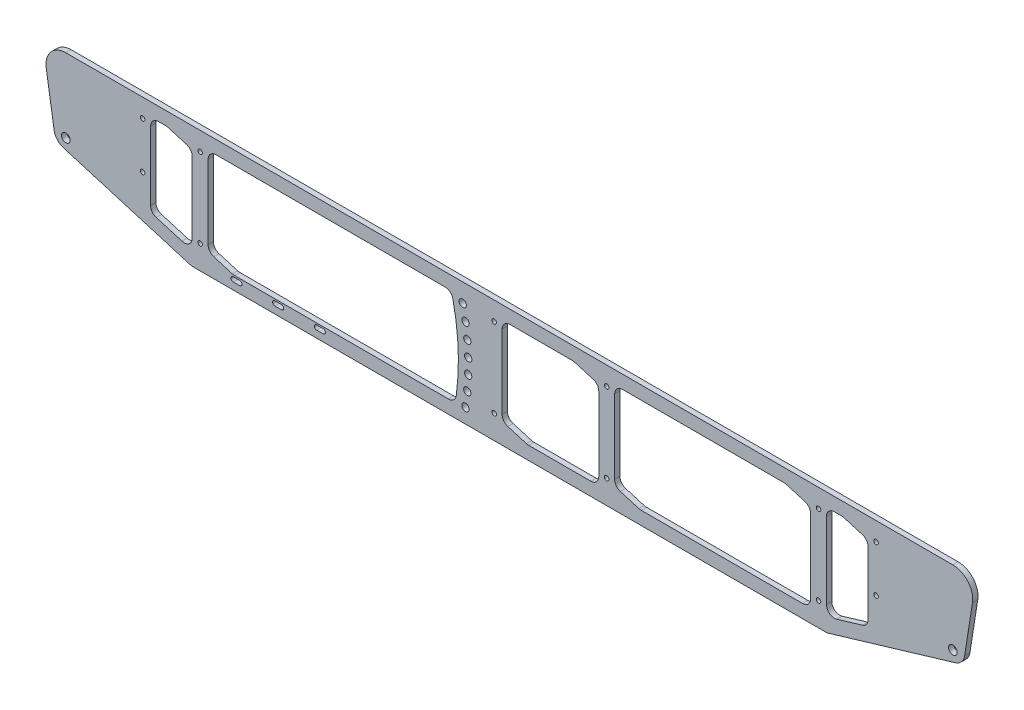
SolidWorks part; units mm, degrees
material "Сплав 2024"
ref_plane "Спереди" through (0, 0, 0) normal (0, 0, 1) x (1, 0, 0)
ref_plane "Сверху" through (0, 0, 0) normal (0, 1, 0) x (1, 0, 0)
ref_plane "Справа" through (0, 0, 0) normal (1, 0, 0) x (0, 0, -1)
sketch "Эскиз1" plane through (0, 0, 0) normal (0, 0, 1) x (1, 0, 0)
  line L0 (-349.8183, 28.6724) -> (-342.9109, -15.3036)
  line L1 (-350, 46) -> (350, 46) construction
  line L2 (-350, 46) -> (-350, -46) construction
  line L3 (-350, -46) -> (350, -46) construction
  line L4 (350, 46) -> (350, -46) construction
  line L5 (-350, 46) -> (350, -46) construction
  line L6 (-350, -46) -> (350, 46) construction
  line L7 (-342.9109, -15.3036) -> (-240, -46)
  line L9 (0, 62.4154) -> (0, -74.3401) construction
  line L10 (-240, -46) -> (240, -46)
  line L12 (-335, 46) -> (335, 46)
  line L15 (342.9109, -15.3036) -> (240, -46)
  line L16 (349.8183, 28.6724) -> (342.9109, -15.3036)
  arc A0 (-335, 46) -> (-349.8183, 28.6724) centre (-335, 31) ccw
  arc A1 (335, 46) -> (349.8183, 28.6724) centre (335, 31) cw
  circle A2 centre (-335, -9.6353) radius 3.25
  circle A3 centre (335, -9.6353) radius 3.25
  point P0 (0, 0)
  point P20 (0, 46)
  point P21 (0, -46)
  dimension "D3" = 30
  dimension "D4" = 6.5
  dimension "D1" = 700
  dimension "D2" = 92
  dimension "D5" = 480
extrude "Бобышка-Вытянуть1" add sketch "Эскиз1" along normal blind 4
sketch "Эскиз2" plane through (0, 0, 4) normal (0, 0, 1) x (1, 0, 0)
  line L0 (0, 49.4785) -> (0, -75.5602) construction
  line L1 (-350, 31) -> (-320, 31) construction
  line L2 (-335, 46) -> (-335, 16) construction
  line L3 (335, 46) -> (335, 16) construction
  line L4 (350, 31) -> (320, 31) construction
  circle A0 centre (-335, 31) radius 15 construction
  arc A1 (-335, 46) -> (-349.8183, 28.6724) centre (-335, 31) ccw construction
  circle A2 centre (-335, 31) radius 10 construction
  circle A4 centre (335, 31) radius 10 construction
  circle A5 centre (335, 31) radius 15 construction
  dimension "D2" = 20
hole_wizard "Отверстие с зазором M32" [suppressed] positions "Эскиз4" profile "Эскиз3" hole size "M3" standard "Ansi Metric"
sketch "Эскиз4" plane through (0, 0, 4) normal (0, 0, 1) x (1, 0, 0)
  line L0 (-335, 46) -> (-335, 16) construction
  line L1 (-350, 31) -> (-320, 31) construction
  line L2 (350, 31) -> (320, 31) construction
  line L3 (335, 46) -> (335, 16) construction
  circle A0 centre (-335, 31) radius 10 construction
  circle A1 centre (335, 31) radius 10 construction
  point P0 (-335, 41)
  point P6 (-345, 31)
  point P10 (-335, 21)
  point P12 (-325, 31)
  point P34 (325, 31)
  point P40 (335, 41)
  point P44 (345, 31)
  point P46 (335, 21)
sketch "Эскиз3" plane through (-335, 41, 4) normal (1, 0, 0) x (0, -1, 0)
  line L0 (0, 0) -> (0, 4)
  line L1 (0, 4) -> (1.7, 4)
  line L2 (1.7, 4) -> (1.7, 0)
  line L5 (1.7, 0) -> (0, 0)
  line L11 (0, -6.35) -> (0, 107.95) construction
  dimension "Диаметр сквозного отверстия" = 3.4
  dimension "Глубина сквозного отверстия" = 4
sketch "Эскиз7" plane through (0, 0, 0) normal (0, 0, -1) x (-1, 0, 0)
  line L1 (240, -46) -> (-240, -46) construction
  arc A1 (349.8183, 28.6724) -> (335, 46) centre (335, 31) ccw construction
  point P4 (215, -7)
  dimension "D1" = 120
  dimension "D2" = 39
hole_wizard "Отверстие с зазором M52" positions "Эскиз9" profile "Эскиз8" hole size "M5" standard "Ansi Metric" end condition through all
sketch "Эскиз9" plane through (0, 0, 0) normal (0, 0, -1) x (-1, 0, 0)
  point P3 (215, -7)
sketch "Эскиз8" plane through (-215, -7, 0) normal (1, 0, 0) x (0, 1, 0)
  line L0 (0, 0) -> (0, 4)
  line L1 (0, 4) -> (2.75, 4)
  line L2 (2.75, 4) -> (2.75, 0)
  line L5 (2.75, 0) -> (0, 0)
  line L11 (0, -6.35) -> (0, 107.95) construction
  dimension "Диаметр сквозного отверстия" = 5.5
  dimension "Глубина сквозного отверстия" = 4
sketch "Эскиз10" plane through (0, 0, 4) normal (0, 0, 1) x (1, 0, 0)
  line L0 (-299.3246, 36) -> (-255.3246, 36)
  line L1 (335, 46) -> (-335, 46) construction
  line L2 (-299.3246, 36) -> (-299.3246, -17.8692)
  line L3 (-299.3246, -17.8692) -> (-244.0344, -34.3612)
  line L4 (0, 46) -> (0, -46) construction
  line L5 (-342.9109, -15.3036) -> (-240, -46) construction
  line L6 (-225.2731, 36) -> (-56.1536, 36)
  line L7 (-238.5404, -36) -> (-53.9475, -36)
  line L8 (-240, -46) -> (240, -46) construction
  line L9 (-255.3246, 36) -> (-240.437, -30.0467)
  line L11 (-300.3246, -20.6159) -> (-300.3246, 44.3841) construction
  line L12 (271.818, 36) -> (271.818, -17.9187)
  line L13 (271.818, -17.9187) -> (224.0901, -33.1261)
  line L14 (271.818, 36) -> (224.0901, 36)
  line L15 (224.0901, 36) -> (224.0901, -33.1261)
  line L17 (212.0901, 36) -> (121.9708, 36)
  line L19 (-272.9676, -25.731) -> (-174.3183, -55.1562) construction
  line L20 (0.7585, 21.0494) -> (0.7585, -36)
  line L21 (0.7585, -36) -> (18.1269, -36)
  line L22 (212.0901, -21.0494) -> (212.0901, 36)
  line L23 (65.0489, 36) -> (65.0489, -21.0494)
  line L24 (75.0489, 21.0494) -> (75.0489, -36)
  line L25 (47.6805, 36) -> (0.7585, 21.0494)
  line L26 (212.0901, -21.0494) -> (165.1682, -36)
  line L27 (-140.8515, 55.5349) -> (-140.8515, -67.5658) construction
  line L28 (75.0489, -36) -> (165.1682, -36)
  line L29 (121.9708, 36) -> (75.0489, 21.0494)
  line L30 (65.0489, -21.0494) -> (18.1269, -36)
  line L31 (-238.5404, -36) -> (-218.7965, -12.3203)
  line L32 (-225.2731, 36) -> (-216.5143, -2.8572)
  line L33 (-164.0688, -36) -> (-228.2742, -36) construction
  line L34 (65.0489, 36) -> (47.6805, 36)
  line L35 (-240.437, -30.0467) -> (-244.0344, -34.3612)
  line L36 (272.818, 44.3841) -> (272.818, -20.6159) construction
  line L37 (223.0901, 43) -> (223.0901, -42) construction
  line L38 (213.0901, 43) -> (213.0901, -42) construction
  arc A0 (-53.9475, -36) -> (-56.1536, 36) centre (-227.2451, -5.276) ccw
  arc A1 (-216.5143, -2.8572) -> (-218.7965, -12.3203) centre (-227.2451, -5.276) cw
  dimension "D4" = 1
  dimension "D5" = 1
  dimension "D2" = 1
  dimension "D10" = 11
  dimension "D12" = 176
  dimension "D1" = 10
  dimension "D3" = 10
  dimension "D6" = 10
  dimension "D7" = 10
  dimension "D8" = 1
  dimension "D9" = 44
  dimension "D11" = 57.0494
extrude "Вырез-Вытянуть3" [suppressed] cut sketch "Эскиз10" against normal through all
fillet "Скругление2" [suppressed] radius 10
fillet "Скругление3" [suppressed] radius 10
sketch "Эскиз14" plane through (0, 0, 4) normal (0, 0, 1) x (1, 0, 0)
  line L0 (0, 59.2479) -> (0, -65.4566) construction
fillet "Скругление4" [suppressed] radius 8
sketch "Эскиз15" plane through (0, 0, 0) normal (0, 0, 1) x (1, 0, 0)
  line L0 (-350, 110.1025) -> (-350, -46) construction
  line L1 (-350, -46) -> (-196.6137, -46) construction
  line L2 (-240, -46) -> (240, -46) construction
  line L3 (350, 94.0601) -> (350, -69.6023) construction
  arc A0 (-335, 46) -> (-349.8183, 28.6724) centre (-335, 31) ccw construction
  arc A1 (349.8183, 28.6724) -> (335, 46) centre (335, 31) ccw construction
sketch "Эскиз17" plane through (0, 0, 0) normal (0, 0, -1) x (-1, 0, 0)
  line L0 (-277, 66.2572) -> (-277, -56.845) construction
  line L1 (-335, 46) -> (335, 46) construction
  line L2 (234.2682, -7) -> (-30.3456, -7) construction
  line L3 (0, 46) -> (0, 69.3185) construction
  line L4 (215, -7) -> (-69.7478, 19.1646) construction
  line L5 (240, -46) -> (-240, -46) construction
  line L6 (215, -7) -> (-66.6882, 1.6064) construction
  line L7 (215, -7) -> (-14.665, -14.0169) construction
  line L8 (215, -7) -> (-40.5191, 32.3282) construction
  line L9 (215, -7) -> (-47.5026, 49.9949) construction
  line L10 (215, -7) -> (-21.1437, -28.6986) construction
  line L11 (215, -7) -> (-22.6665, -43.5804) construction
  arc A0 (-335, 46) -> (-349.8183, 28.6724) centre (-335, 31) ccw construction
  arc A1 (36.6847, -52.3836) -> (42.8196, 57.8837) centre (215, -7) cw construction
  point P2 (-277, 31)
  point P3 (-277, -4)
  point P9 (277, 31)
  point P10 (277, -4)
  point P20 (31.7713, 9.83)
  dimension "D3" = 58
  dimension "D4" = 184
  dimension "D1" = 15
  dimension "D2" = 35
  dimension "D5" = 55.83
  dimension "D6" = 1.75
  dimension "D7" = 3.5
  dimension "D8" = 3.5
  dimension "D9" = 3.5
  dimension "D10" = 1.75
  dimension "D11" = 3.5
  dimension "D12" = 3.5
hole_wizard "Отверстие с зазором M33" [suppressed] positions "Эскиз19" profile "Эскиз18" hole size "M3" standard "Ansi Metric"
sketch "Эскиз19" [suppressed] plane through (0, 0, 0) normal (0, 0, -1) x (-1, 0, 0)
  point P0 (-277, 31)
  point P5 (-277, -4)
  point P8 (277, -4)
  point P11 (277, 31)
sketch "Эскиз18" plane through (277, 31, 0) normal (1, 0, 0) x (0, 1, 0)
  line L0 (0, 0) -> (0, 4)
  line L1 (0, 4) -> (1.7, 4)
  line L2 (1.7, 4) -> (1.7, 0)
  line L5 (1.7, 0) -> (0, 0)
  line L11 (0, -6.35) -> (0, 107.95) construction
  dimension "Диаметр сквозного отверстия" = 3.4
  dimension "Глубина сквозного отверстия" = 4
hole_wizard "Отверстие с зазором M53" positions "Эскиз21" profile "Эскиз20" hole size "M5" standard "Ansi Metric" end condition through all
sketch "Эскиз21" plane through (0, 0, 0) normal (0, 0, -1) x (-1, 0, 0)
  line L0 (215, -7) -> (-47.5026, 49.9949) construction
  line L1 (215, -7) -> (-40.5191, 32.3282) construction
  line L2 (215, -7) -> (-66.6882, 1.6064) construction
  line L3 (215, -7) -> (-14.665, -14.0169) construction
  line L4 (215, -7) -> (-21.1437, -28.6986) construction
  line L5 (215, -7) -> (-22.6665, -43.5804) construction
  arc A0 (42.8196, 57.8837) -> (36.6847, -52.3836) centre (215, -7) ccw construction
  point P0 (31.7713, 9.83)
  point P3 (35.1895, 32.0407)
  point P10 (33.1415, 20.9907)
  point P14 (31.0858, -1.3809)
  point P18 (31.0858, -12.6191)
  point P22 (31.7719, -23.8363)
  point P26 (33.1415, -34.9907)
sketch "Эскиз20" plane through (-31.7713, 9.83, 0) normal (1, 0, 0) x (0, 1, 0)
  line L0 (0, 0) -> (0, 4)
  line L1 (0, 4) -> (2.75, 4)
  line L2 (2.75, 4) -> (2.75, 0)
  line L5 (2.75, 0) -> (0, 0)
  line L11 (0, -6.35) -> (0, 107.95) construction
  dimension "Диаметр сквозного отверстия" = 5.5
  dimension "Глубина сквозного отверстия" = 4
fillet "Скругление5" radius 10 4 edges at (342.9109, -15.3036, 2) (240, -46, 2) (-342.9109, -15.3036, 2) (-240, -46, 2)
sketch "Эскиз22" plane through (0, 0, 0) normal (0, 0, -1) x (-1, 0, 0)
  line L0 (-227.5404, -36) -> (-98.7059, -36)
  line L1 (-79.5404, -30.2833) -> (-79.5404, 36)
  line L2 (-79.5404, 36) -> (-208.3748, 36)
  line L3 (-227.5404, 30.2833) -> (-227.5404, -36)
  line L4 (-241.3987, -45.5828) -> (-336.8687, -17.1059) construction
  line L5 (227.54, -30.2833) -> (208.3744, -36)
  line L6 (-271, 30.2833) -> (-251.8344, 36)
  line L7 (238.5404, -46) -> (-238.5404, -46) construction
  line L8 (-335, 46) -> (335, 46) construction
  line L9 (-67.5404, -36) -> (-13.7059, -36)
  line L10 (5.4596, -30.2833) -> (5.4596, 36)
  line L11 (5.4596, 36) -> (-48.3748, 36)
  line L12 (-67.5404, 30.2833) -> (-67.5404, -36)
  line L13 (-227.5404, 30.2833) -> (-208.3748, 36)
  line L14 (-79.5404, -30.2833) -> (-98.7059, -36)
  line L15 (40.8987, -36) -> (208.3744, -36)
  line L16 (43.8181, 36) -> (227.54, 36)
  line L17 (227.54, 36) -> (227.54, -30.2833)
  line L19 (-67.5404, 30.2833) -> (-48.3748, 36)
  line L20 (-13.7059, -36) -> (5.4596, -30.2833)
  line L21 (239.54, 30.2833) -> (258.7056, 36)
  line L23 (-272, 42) -> (-272, -23) construction
  line L24 (-239.5404, 36) -> (-251.8344, 36)
  line L25 (-271, 30.2833) -> (-271, -26.3179)
  line L26 (-228.5404, 42) -> (-228.5404, -43) construction
  line L27 (-271, -26.3179) -> (-239.5404, -35.7017)
  line L28 (-239.5404, -35.7017) -> (-239.5404, 36)
  line L29 (-68.5404, 42) -> (-68.5404, -43) construction
  line L30 (258.7056, 36) -> (271, 36)
  line L31 (271, 36) -> (271, -26.3179)
  line L32 (271, -26.3179) -> (239.54, -35.7018)
  line L33 (239.54, -35.7018) -> (239.54, 30.2833)
  line L34 (336.8687, -17.1059) -> (241.3987, -45.5828) construction
  line L35 (6.4596, 42) -> (6.4596, -43) construction
  line L37 (272, -23) -> (272, 42) construction
  arc A0 (40.8987, -36) -> (43.8181, 36) centre (215, -7) cw
  dimension "D3" = 176.5
  dimension "D4" = 12
  dimension "D1" = 10
  dimension "D2" = 10
  dimension "D6" = 10
  dimension "D7" = 12
  dimension "D8" = 12
  dimension "D9" = 10
  dimension "D10" = 1
  dimension "D11" = 1
  dimension "D12" = 1
  dimension "D13" = 1
  dimension "D14" = 1
  dimension "D15" = 20
  dimension "D16" = 31.46
extrude "Вырез-Вытянуть4" cut sketch "Эскиз22" against normal through all
fillet "Скругление7" radius 6 27 edges at (-239.54, -35.7018, 2) (-271, -26.3179, 2) (-271, 36, 2) (-227.54, 36, 2) (-258.7056, 36, 2) (-239.54, 30.2833, 2) (-43.8181, 36, 2) (-40.8987, -36, 2) (67.5404, -36, 2) (-5.4596, -30.2833, 2) (13.7059, -36, 2) (-5.4596, 36, 2) (48.3748, 36, 2) (67.5404, 30.2833, 2) (227.5404, 30.2833, 2) (208.3748, 36, 2) (79.5404, 36, 2) (79.5404, -30.2833, 2) (98.7059, -36, 2) (227.5404, -36, 2) (239.5404, -35.7017, 2) (271, -26.3179, 2) (271, 30.2833, 2) (251.8344, 36, 2) (239.5404, 36, 2) (-208.3744, -36, 2) (-227.54, -30.2833, 2)
hole_wizard "Отверстие с зазором M34" positions "Эскиз24" profile "Эскиз23" hole size "M3" standard "Ansi Metric" end condition through all
sketch "Эскиз24" plane through (0, 0, 0) normal (0, 0, -1) x (-1, 0, 0)
  point P0 (-233.5404, 32)
  point P3 (-233.5404, -28)
  point P6 (-73.5404, -28)
  point P9 (-73.5404, 32)
  point P12 (11.4596, 32)
  point P15 (11.4596, -28)
  point P19 (277, 32)
  point P22 (277, -3)
  point P25 (-277, 32)
  point P28 (-277, -3)
  point P31 (233.54, -28)
  point P34 (233.54, 32)
sketch "Эскиз23" plane through (233.5404, 32, 0) normal (1, 0, 0) x (0, 1, 0)
  line L0 (0, 0) -> (0, 4)
  line L1 (0, 4) -> (1.7, 4)
  line L2 (1.7, 4) -> (1.7, 0)
  line L5 (1.7, 0) -> (0, 0)
  line L11 (0, -6.35) -> (0, 107.95) construction
  dimension "Диаметр сквозного отверстия" = 3.4
  dimension "Глубина сквозного отверстия" = 4
sketch "Эскиз25" plane through (0, 0, 4) normal (0, 0, 1) x (1, 0, 0)
  line L0 (-206.1415, -27.8745) -> (-206.1415, -52.0788) construction
  line L1 (-174.6415, -27.8745) -> (-174.6415, -52.0788) construction
  line L2 (-143.1415, -27.8745) -> (-143.1415, -52.0788) construction
  line L3 (-203.929, -39) -> (-45.24, -39) construction
  line L5 (-208.6415, -39) -> (-203.6415, -39) construction
  line L6 (-208.6415, -37.3) -> (-203.6415, -37.3)
  line L7 (-208.6415, -40.7) -> (-203.6415, -40.7)
  line L8 (-177.1415, -39) -> (-172.1415, -39) construction
  line L9 (-177.1415, -37.3) -> (-172.1415, -37.3)
  line L10 (-177.1415, -40.7) -> (-172.1415, -40.7)
  line L11 (-140.6415, -39) -> (-145.6415, -39) construction
  line L12 (-140.6415, -40.7) -> (-145.6415, -40.7)
  line L13 (-140.6415, -37.3) -> (-145.6415, -37.3)
  line L14 (-46.0584, -36) -> (-207.4987, -36) construction
  arc A0 (-208.6415, -37.3) -> (-208.6415, -40.7) centre (-208.6415, -39) ccw
  arc A1 (-203.6415, -40.7) -> (-203.6415, -37.3) centre (-203.6415, -39) ccw
  arc A2 (-177.1415, -37.3) -> (-177.1415, -40.7) centre (-177.1415, -39) ccw
  arc A3 (-172.1415, -40.7) -> (-172.1415, -37.3) centre (-172.1415, -39) ccw
  arc A4 (-140.6415, -40.7) -> (-140.6415, -37.3) centre (-140.6415, -39) ccw
  arc A5 (-145.6415, -37.3) -> (-145.6415, -40.7) centre (-145.6415, -39) ccw
  circle A6 centre (-33.1415, -34.9907) radius 2.75 construction
  point P12 (-206.1415, -39)
  point P19 (-174.6415, -39)
  point P25 (-143.1415, -39)
  dimension "D5" = 1.7
  dimension "D8" = 1.7
  dimension "D9" = 1.7
  dimension "D1" = 31.5
  dimension "D2" = 31.5
  dimension "D3" = 3
  dimension "D4" = 5
  dimension "D6" = 5
  dimension "D7" = 5
  dimension "D10" = 110
extrude "Вырез-Вытянуть5" cut sketch "Эскиз25" against normal through all
